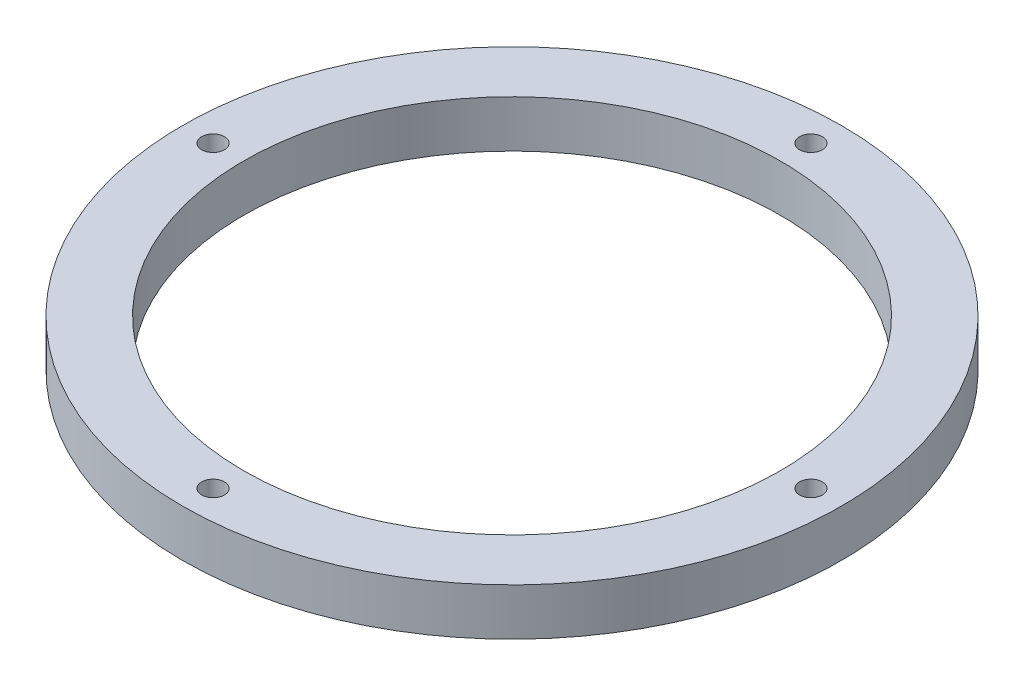
SolidWorks part; units mm, degrees
ref_plane "Front Plane" through (0, 0, 0) normal (0, 0, 1) x (1, 0, 0)
ref_plane "Top Plane" through (0, 0, 0) normal (0, 1, 0) x (1, 0, 0)
ref_plane "Right Plane" through (0, 0, 0) normal (1, 0, 0) x (0, 0, -1)
sketch "Sketch2" plane through (0, 0, 0) normal (0, 1, 0) x (1, 0, 0)
  circle A0 centre (0, 0) radius 70
extrude "Boss-Extrude1" add sketch "Sketch2" along normal blind 10 contours A0
sketch "Sketch3" plane through (0, 10, 0) normal (0, 1, 0) x (1, 0, 0)
  circle A0 centre (0, 0) radius 57
extrude "Cut-Extrude1" cut sketch "Sketch3" against normal blind 10
sketch "Sketch4" plane through (0, 10, 0) normal (0, 1, 0) x (1, 0, 0)
  circle A1 centre (-63.5, 0) radius 2.4215
  circle A3 centre (0, 63.5) radius 2.4215
  circle A4 centre (63.5, 0) radius 2.4215
  circle A5 centre (0, -63.5) radius 2.4215
  point P13 (0, 0)
  dimension "D1" = 4
extrude "Cut-Extrude2" cut sketch "Sketch4" against normal blind 10
